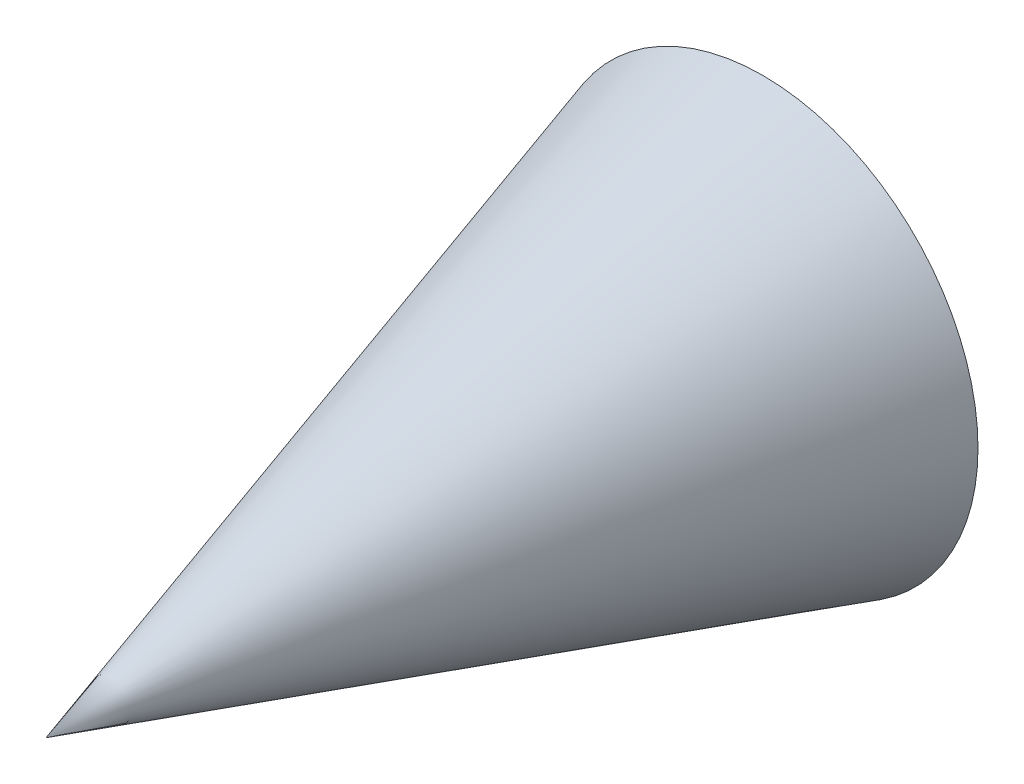
SolidWorks part; units mm, degrees
ref_plane "Front Plane" through (0, 0, 0) normal (0, 0, 1) x (1, 0, 0)
ref_plane "Top Plane" through (0, 0, 0) normal (0, 1, 0) x (1, 0, 0)
ref_plane "Right Plane" through (0, 0, 0) normal (1, 0, 0) x (0, 0, -1)
sketch "Sketch1" plane through (0, 0, 0) normal (1, 0, 0) x (0, 0, -1)
  line L0 (0, 0) -> (0, 30)
  line L1 (0, 30) -> (-100, 0)
  line L2 (-100, 0) -> (0, 0)
  line L3 (0, 0) -> (-110, 0) construction
revolve "Cone" add sketch "Sketch1" angle 360 about L3
